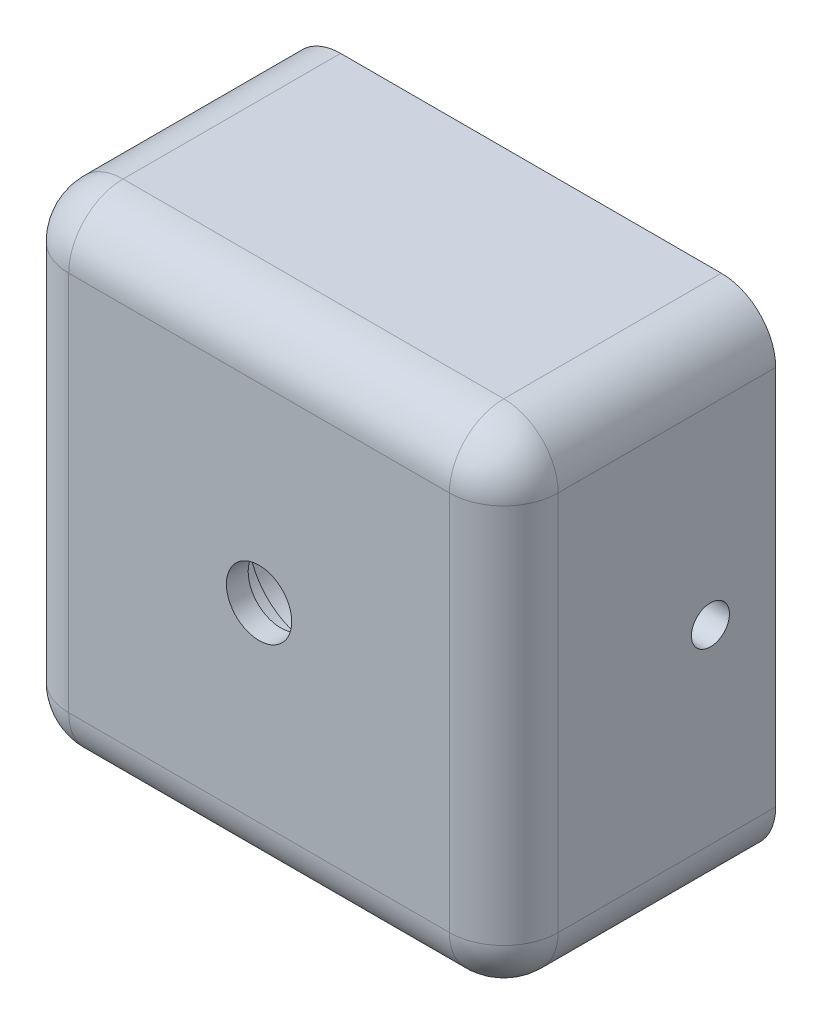
SolidWorks part; units mm, degrees
ref_plane "Alzado" through (0, 0, 0) normal (0, 0, 1) x (1, 0, 0)
ref_plane "Planta" through (0, 0, 0) normal (0, 1, 0) x (1, 0, 0)
ref_plane "Vista lateral" through (0, 0, 0) normal (1, 0, 0) x (0, 0, -1)
sketch "Croquis1" plane through (0, 0, 0) normal (0, 0, 1) x (1, 0, 0)
  line L1 (-22.5, 22.5) -> (22.5, 22.5)
  line L2 (-22.5, 22.5) -> (-22.5, -22.5)
  line L3 (-22.5, -22.5) -> (22.5, -22.5)
  line L4 (22.5, 22.5) -> (22.5, -22.5)
  line L5 (-22.5, 22.5) -> (22.5, -22.5) construction
  line L6 (-22.5, -22.5) -> (22.5, 22.5) construction
  point P0 (0, 0)
  dimension "D1" = 45
  dimension "D2" = 45
extrude "Saliente-Extruir1" add sketch "Croquis1" along normal blind 25
sketch "Croquis2" plane through (0, 0, 0) normal (0, 0, -1) x (-1, 0, 0)
  line L0 (-22.5, 22.5) -> (22.5, 22.5) construction
  line L1 (-16.5, 16.5) -> (16.5, 16.5)
  line L2 (-16.5, 16.5) -> (-16.5, -16.5)
  line L3 (-16.5, -16.5) -> (16.5, -16.5)
  line L4 (16.5, 16.5) -> (16.5, -16.5)
  line L5 (-16.5, 16.5) -> (16.5, -16.5) construction
  line L6 (-16.5, -16.5) -> (16.5, 16.5) construction
  line L7 (-22.5, -22.5) -> (-22.5, 22.5) construction
  point P0 (0, 0)
  dimension "D1" = 6
  dimension "D2" = 6
extrude "Cortar-Extruir1" cut sketch "Croquis2" against normal blind 20
sketch "Croquis3" plane through (0, 0, 20) normal (0, 0, -1) x (-1, 0, 0)
  circle A0 centre (0, 0) radius 6
  dimension "D1" = 12
extrude "Cortar-Extruir2" cut sketch "Croquis3" against normal blind 3
sketch "Croquis4" plane through (0, 0, 20) normal (0, 0, -1) x (-1, 0, 0)
  circle A0 centre (0, 0) radius 3
  dimension "D1" = 6
extrude "Cortar-Extruir3" cut sketch "Croquis4" against normal blind 6
sketch "Croquis5" plane through (22.5, 0, 0) normal (1, 0, 0) x (0, 0, -1)
  line L0 (-12, 22.5) -> (-12, -22.5) construction
  line L1 (-25, 22.5) -> (0, 22.5) construction
  line L2 (-25, -22.5) -> (0, -22.5) construction
  line L3 (-25, 0) -> (0, 0) construction
  line L4 (-25, -22.5) -> (-25, 22.5) construction
  line L5 (0, -22.5) -> (0, 22.5) construction
  line L6 (-6, 22.5) -> (-6, -22.5) construction
  circle A0 centre (-6, 0) radius 1.75
  dimension "D3" = 3.5
  dimension "D1" = 12
  dimension "D2" = 6
extrude "Cortar-Extruir4" cut sketch "Croquis5" against normal blind 56
sketch "Croquis6" plane through (16.5, 0, 0) normal (-1, 0, 0) x (0, 0, 1)
  line L1 (7.963, -3.4) -> (9.926, 0)
  line L2 (9.926, 0) -> (7.963, 3.4)
  line L3 (7.963, 3.4) -> (4.037, 3.4)
  line L4 (4.037, 3.4) -> (2.074, 0)
  line L5 (2.074, 0) -> (4.037, -3.4)
  line L6 (4.037, -3.4) -> (7.963, -3.4)
  circle A0 centre (6, 0) radius 3.4 construction
  point P1 (1.9585, 0)
  dimension "D2" = 2.074
  dimension "D1" = 6.8
extrude "Cortar-Extruir5" cut sketch "Croquis6" against normal blind 2
sketch "Croquis7" plane through (-16.5, 0, 0) normal (1, 0, 0) x (0, 0, -1)
  line L1 (-2.074, 0) -> (-4.037, 3.4)
  line L2 (-4.037, 3.4) -> (-7.963, 3.4)
  line L3 (-7.963, 3.4) -> (-9.926, 0)
  line L4 (-9.926, 0) -> (-7.963, -3.4)
  line L5 (-7.963, -3.4) -> (-4.037, -3.4)
  line L6 (-4.037, -3.4) -> (-2.074, 0)
  circle A0 centre (-6, 0) radius 3.4 construction
  dimension "D1" = 6.8
  dimension "D2" = 2.074
extrude "Cortar-Extruir6" cut sketch "Croquis7" against normal blind 2
fillet "Redondeo1" radius 5 8 edges at (-16.5, 16.5, 10) (-22.5, 22.5, 12.5) (-16.5, -16.5, 10) (-22.5, -22.5, 12.5) (16.5, -16.5, 10) (22.5, -22.5, 12.5) (22.5, 22.5, 12.5) (16.5, 16.5, 10)
fillet "Redondeo2" radius 5 8 edges at (21.0355, -21.0355, 25) (0, -22.5, 25) (-21.0355, -21.0355, 25) (-22.5, 0, 25) (-21.0355, 21.0355, 25) (0, 22.5, 25) (21.0355, 21.0355, 25) (22.5, 0, 25)
